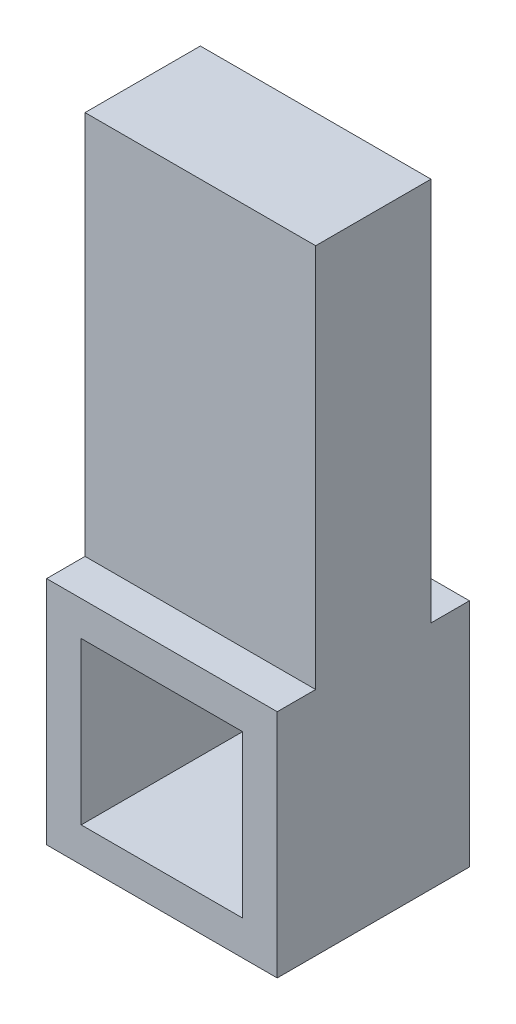
SolidWorks part; units mm, degrees
ref_plane "Front Plane" through (0, 0, 0) normal (0, 0, 1) x (1, 0, 0)
ref_plane "Top Plane" through (0, 0, 0) normal (0, 1, 0) x (1, 0, 0)
ref_plane "Right Plane" through (0, 0, 0) normal (1, 0, 0) x (0, 0, -1)
sketch "Sketch1" plane through (0, 0, 0) normal (0, 0, 1) x (1, 0, 0)
  line L1 (3, -3) -> (-3, -3)
  line L2 (3, -3) -> (3, 3)
  line L3 (3, 3) -> (-3, 3)
  line L4 (-3, -3) -> (-3, 3)
  line L5 (3, -3) -> (-3, 3) construction
  line L6 (3, 3) -> (-3, -3) construction
  line L7 (2.1, -2.1) -> (-2.1, -2.1)
  line L8 (2.1, -2.1) -> (2.1, 2.1)
  line L9 (2.1, 2.1) -> (-2.1, 2.1)
  line L10 (-2.1, -2.1) -> (-2.1, 2.1)
  line L11 (2.1, -2.1) -> (-2.1, 2.1) construction
  line L12 (2.1, 2.1) -> (-2.1, -2.1) construction
  point P0 (0, 0)
  point P6 (0, 0)
  dimension "D1" = 6
  dimension "D2" = 6
  dimension "D3" = 4.2
extrude "Boss-Extrude1" add sketch "Sketch1" along normal mid plane 5
sketch "Sketch2" plane through (0, 0, 0) normal (0, 0, 1) x (1, 0, 0)
  line L0 (-3, 3) -> (3, 3)
  line L1 (3, 3) -> (3, 13)
  line L2 (3, 13) -> (-3, 13)
  line L3 (-3, 13) -> (-3, 3)
  line L4 (0, 13) -> (0, 3) construction
  line L6 (0, -2.75) -> (0, 2.75) construction
  dimension "D1" = 6
  dimension "D2" = 10
extrude "Boss-Extrude2" add sketch "Sketch2" along normal mid plane 3
